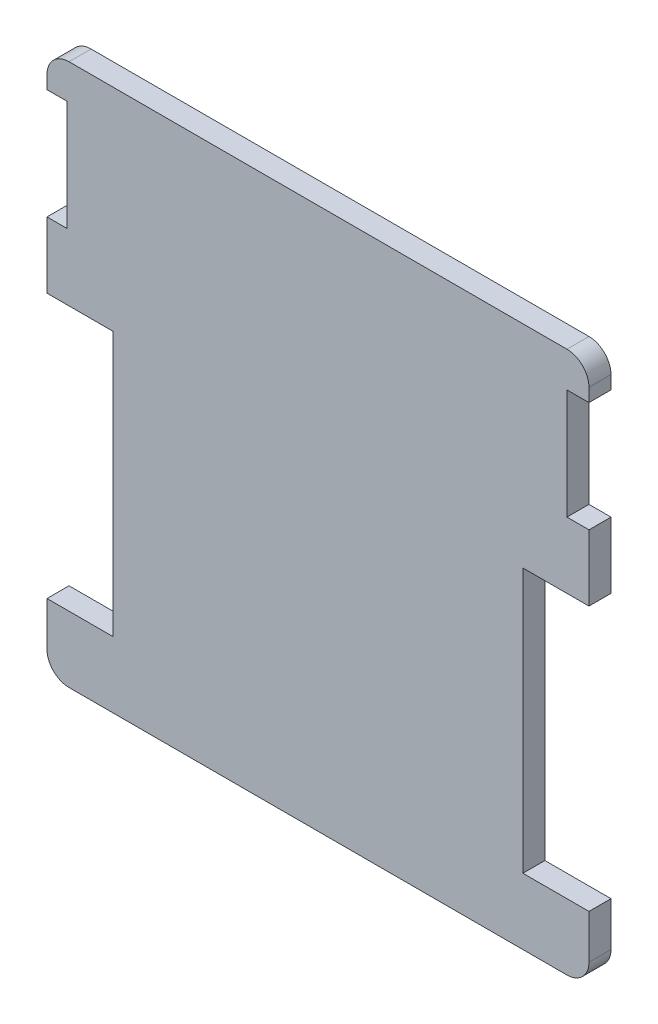
SolidWorks part; units mm, degrees
ref_plane "Plano frontal" through (0, 0, 0) normal (0, 0, 1) x (1, 0, 0)
ref_plane "Plano superior" through (0, 0, 0) normal (0, 1, 0) x (1, 0, 0)
ref_plane "Plano direito" through (0, 0, 0) normal (1, 0, 0) x (0, 0, -1)
sketch "Esboço1" plane through (0, 0, 0) normal (0, 0, 1) x (1, 0, 0)
  line L1 (-47.8109, 58.4855) -> (65.1891, 58.4855)
  line L2 (-52.8109, 53.4855) -> (-52.8109, -59.5145)
  line L3 (-47.8109, -64.5145) -> (65.1891, -64.5145)
  line L4 (70.1891, 53.4855) -> (70.1891, -59.5145)
  arc A0 (70.1891, 53.4855) -> (65.1891, 58.4855) centre (65.1891, 53.4855) ccw
  arc A1 (70.1891, -59.5145) -> (65.1891, -64.5145) centre (65.1891, -59.5145) cw
  arc A2 (-52.8109, -59.5145) -> (-47.8109, -64.5145) centre (-47.8109, -59.5145) ccw
  arc A3 (-52.8109, 53.4855) -> (-47.8109, 58.4855) centre (-47.8109, 53.4855) cw
  dimension "D1" = 5
extrude "Ressalto-extrusão1" add sketch "Esboço1" along normal blind 5
sketch "Esboço4" plane through (0, 0, 5) normal (0, 0, 1) x (1, 0, 0)
  line L0 (-52.8109, 53.4855) -> (-52.8109, -59.5145) construction
  line L1 (-52.8109, 50.4855) -> (-48.3154, 50.4855)
  line L2 (-52.8109, 50.4855) -> (-52.8109, 25.4855)
  line L3 (-52.8109, 25.4855) -> (-48.3154, 25.4855)
  line L4 (-48.3154, 50.4855) -> (-48.3154, 25.4855)
  line L5 (65.1891, 58.4855) -> (-47.8109, 58.4855) construction
  dimension "D1" = 8
extrude "Corte-extrusão2" cut sketch "Esboço4" against normal blind 5
sketch "Esboço11" plane through (0, 0, 5) normal (0, 0, 1) x (1, 0, 0)
  line L0 (70.1891, -59.5145) -> (70.1891, 53.4855) construction
  line L1 (70.1891, 50.4855) -> (65.1891, 50.4855)
  line L2 (70.1891, 50.4855) -> (70.1891, 25.4855)
  line L3 (70.1891, 25.4855) -> (65.1891, 25.4855)
  line L4 (65.1891, 50.4855) -> (65.1891, 25.4855)
  line L5 (65.1891, 58.4855) -> (-47.8109, 58.4855) construction
  dimension "D1" = 8
extrude "Corte-extrusão8" cut sketch "Esboço11" against normal blind 10
sketch "Esboço24" plane through (0, 0, 5) normal (0, 0, 1) x (1, 0, 0)
  line L0 (-52.8109, 25.4855) -> (-52.8109, -59.5145) construction
  line L1 (-52.8109, -49.5145) -> (-37.8109, -49.5145)
  line L2 (-52.8109, -49.5145) -> (-52.8109, 10.4855)
  line L3 (-52.8109, 10.4855) -> (-37.8109, 10.4855)
  line L4 (-37.8109, -49.5145) -> (-37.8109, 10.4855)
  line L6 (-47.8109, -64.5145) -> (65.1891, -64.5145) construction
  dimension "D1" = 15
extrude "Corte-extrusão14" cut sketch "Esboço24" against normal blind 10
sketch "Esboço27" plane through (0, 0, 5) normal (0, 0, 1) x (1, 0, 0)
  line L0 (70.1891, -59.5145) -> (70.1891, 25.4855) construction
  line L1 (70.1891, -49.5145) -> (55.1891, -49.5145)
  line L2 (70.1891, -49.5145) -> (70.1891, 10.4855)
  line L3 (70.1891, 10.4855) -> (55.1891, 10.4855)
  line L4 (55.1891, -49.5145) -> (55.1891, 10.4855)
  line L5 (-52.8109, -49.5145) -> (-37.8109, -49.5145) construction
  line L6 (-47.8109, -64.5145) -> (65.1891, -64.5145) construction
  dimension "D1" = 15
  dimension "D2" = 15
extrude "Corte-extrusão16" cut sketch "Esboço27" against normal blind 25
